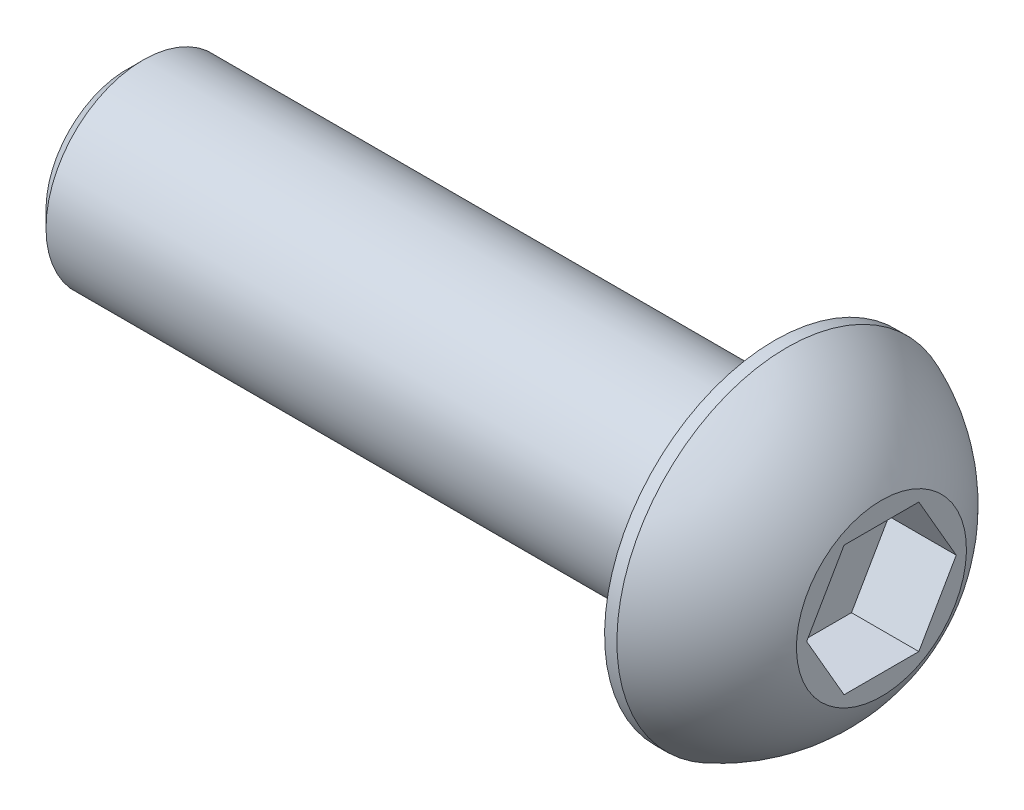
SolidWorks part; units mm, degrees
material "AISI 1020"
ref_plane "Front Plane" through (0, 0, 0) normal (0, 0, 1) x (1, 0, 0)
ref_plane "Top Plane" through (0, 0, 0) normal (0, 1, 0) x (1, 0, 0)
ref_plane "Right Plane" through (0, 0, 0) normal (1, 0, 0) x (0, 0, -1)
sketch "Sketch1" plane through (0, 0, 0) normal (0, 0, 1) x (1, 0, 0)
  line L0 (0, 0) -> (-23.3, 0) construction
  line L1 (0, 0) -> (0, 2.625)
  line L2 (-2.92, 5.25) -> (-3.3, 5.25)
  line L3 (-3.3, 5.25) -> (-3.3, 3)
  line L4 (-3.3, 3) -> (-23.3, 3)
  line L5 (-23.3, 3) -> (-23.3, 0)
  line L6 (-23.3, 0) -> (0, 0)
  arc A0 (0, 2.625) -> (-2.92, 5.25) centre (-4.9997, 0) ccw
  dimension "D6" = 5.25
  dimension "Diam" = 6
  dimension "Ilgis" = 20
  dimension "G_sonas" = 0.38
  dimension "G_diam" = 10.5
  dimension "G_plotis" = 3.3
revolve "Revolve1" add sketch "Sketch1" angle 360 about L0
cosmetic thread "Cosmetic Thread1" parameters "Sr_diam"=5
sketch "Sketch2" plane through (0, 0, 0) normal (1, 0, 0) x (0, 0, -1)
  line L1 (2.3094, 0) -> (1.1547, 2)
  line L2 (1.1547, 2) -> (-1.1547, 2)
  line L3 (-1.1547, 2) -> (-2.3094, 0)
  line L4 (-2.3094, 0) -> (-1.1547, -2)
  line L5 (-1.1547, -2) -> (1.1547, -2)
  line L6 (1.1547, -2) -> (2.3094, 0)
  circle A0 centre (0, 0) radius 2 construction
  dimension "R_dydis" = 4
extrude "Cut-Extrude1" cut sketch "Sketch2" against normal blind 2.08
chamfer "Chamfer1" distance 0.5 angle 45 1 edges at (-23.3, 3, 0)
equation "\"D6@Sketch1\" = \"G_diam@Sketch1\" / 2"
